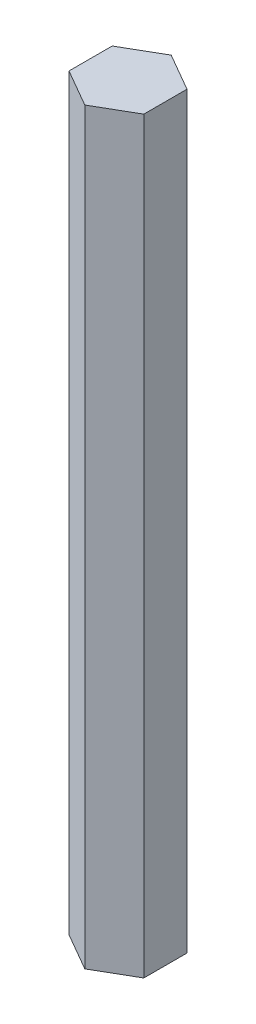
SolidWorks part; units mm, degrees
material "1060 Alloy"
ref_plane "Front Plane" through (0, 0, 0) normal (0, 0, 1) x (1, 0, 0)
ref_plane "Top Plane" through (0, 0, 0) normal (0, 1, 0) x (1, 0, 0)
ref_plane "Right Plane" through (0, 0, 0) normal (1, 0, 0) x (0, 0, -1)
sketch "Sketch1" plane through (0, 0, 0) normal (0, 1, 0) x (1, 0, 0)
  line L1 (0, 7.3323) -> (-6.35, 3.6662)
  line L2 (-6.35, 3.6662) -> (-6.35, -3.6662)
  line L3 (-6.35, -3.6662) -> (0, -7.3323)
  line L4 (0, -7.3323) -> (6.35, -3.6662)
  line L5 (6.35, -3.6662) -> (6.35, 3.6662)
  line L6 (6.35, 3.6662) -> (0, 7.3323)
  circle A0 centre (0, 0) radius 6.35 construction
  dimension "D1" = 12.7
extrude "Boss-Extrude1" add sketch "Sketch1" along normal blind 127
sketch "Sketch2" plane through (0, 127, 0) normal (0, 1, 0) x (1, 0, 0)
  circle A0 centre (0, 0) radius 6.35
